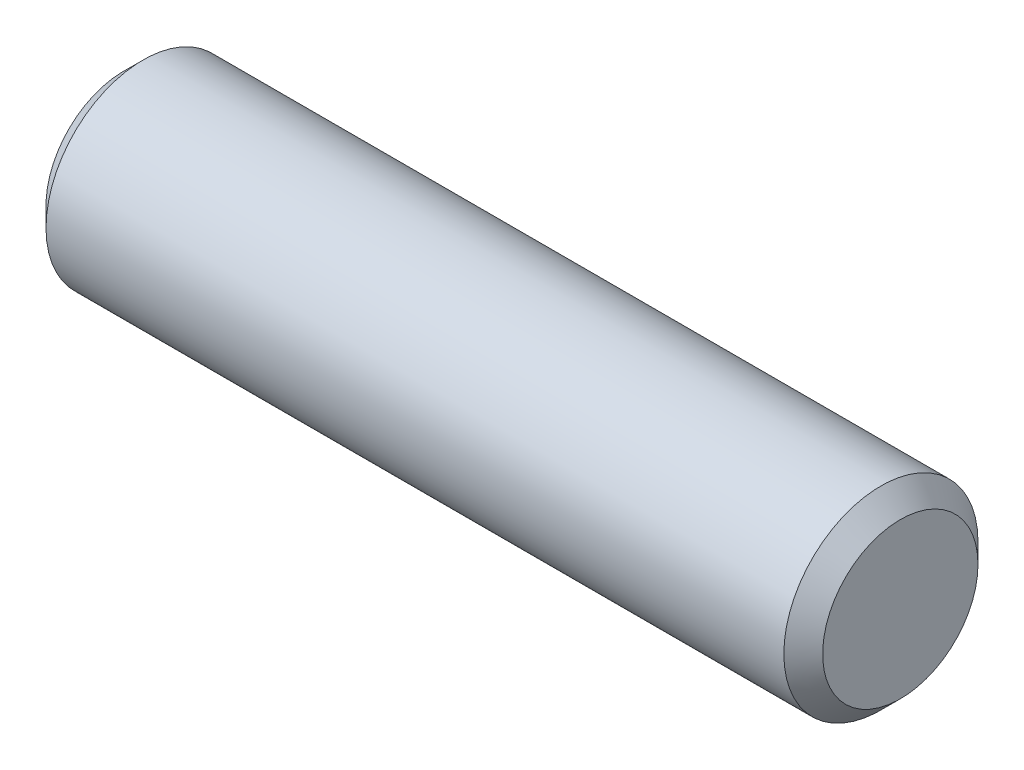
SolidWorks part; units mm, degrees
material "Alloy Steel"
ref_plane "Front" through (0, 0, 0) normal (0, 0, 1) x (1, 0, 0)
ref_plane "Top" through (0, 0, 0) normal (0, 1, 0) x (1, 0, 0)
ref_plane "Right" through (0, 0, 0) normal (1, 0, 0) x (0, 0, -1)
sketch "Sketch1" plane through (0, 0, 0) normal (0, 0, 1) x (1, 0, 0)
  line L0 (-12.7, 0) -> (12.7, 0) construction
  line L1 (12.7, 3.175) -> (12.7, -3.175) construction
  line L2 (-12.7, 3.175) -> (-12.7, -3.175) construction
  dimension "Length" = 25.4
  dimension "Diameter" = 6.35
sketch "Sketch2" plane through (0, 0, 0) normal (1, 0, 0) x (0, 0, -1)
  circle A0 centre (0, 0) radius 3.175
extrude "Extrude1" add sketch "Sketch2" against normal up to vertex (12.7 mm away) and the other way up to vertex (12.7 mm away) up to point (-12.7, 3.175, 0) other way up to point (12.7, 3.175, 0)
chamfer "Chamfer1" distance 0.635 angle 45 2 edges at (12.7, 0, -3.175) (-12.7, 0, -3.175)
equation "\"D1@Chamfer1\" = \"Diameter@Sketch1\"*.1"
